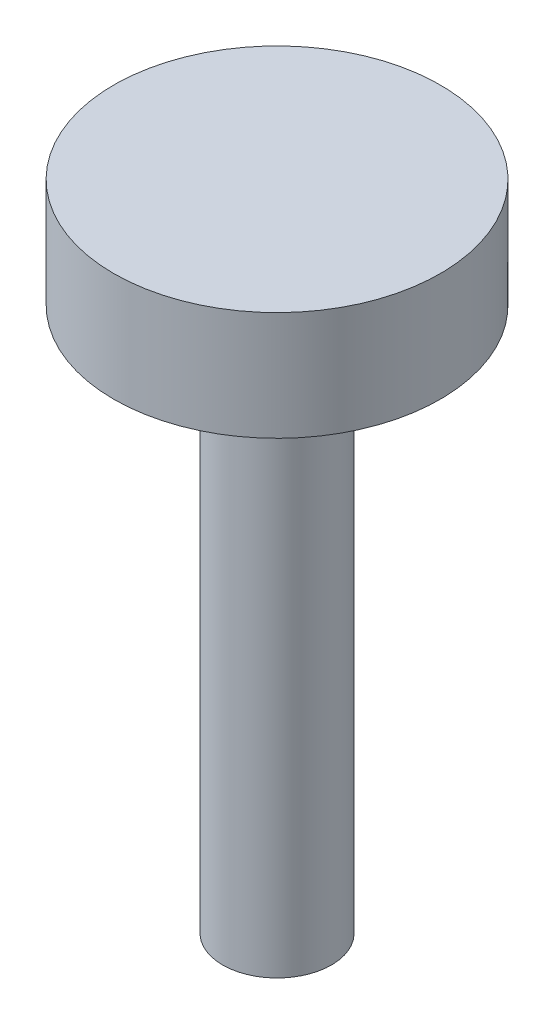
SolidWorks part; units mm, degrees
ref_plane "Front Plane" through (0, 0, 0) normal (0, 0, 1) x (1, 0, 0)
ref_plane "Top Plane" through (0, 0, 0) normal (0, 1, 0) x (1, 0, 0)
ref_plane "Right Plane" through (0, 0, 0) normal (1, 0, 0) x (0, 0, -1)
sketch "Sketch1" plane through (0, 0, 0) normal (0, 1, 0) x (1, 0, 0)
  circle A0 centre (0, 0) radius 2.5
  dimension "D1" = 5
extrude "Boss-Extrude1" add sketch "Sketch1" along normal blind 25
sketch "Sketch3" plane through (0, 25, 0) normal (0, 1, 0) x (1, 0, 0)
  circle A0 centre (0, 0) radius 7.5
  dimension "D1" = 15
extrude "Boss-Extrude2" add sketch "Sketch3" along normal blind 5
